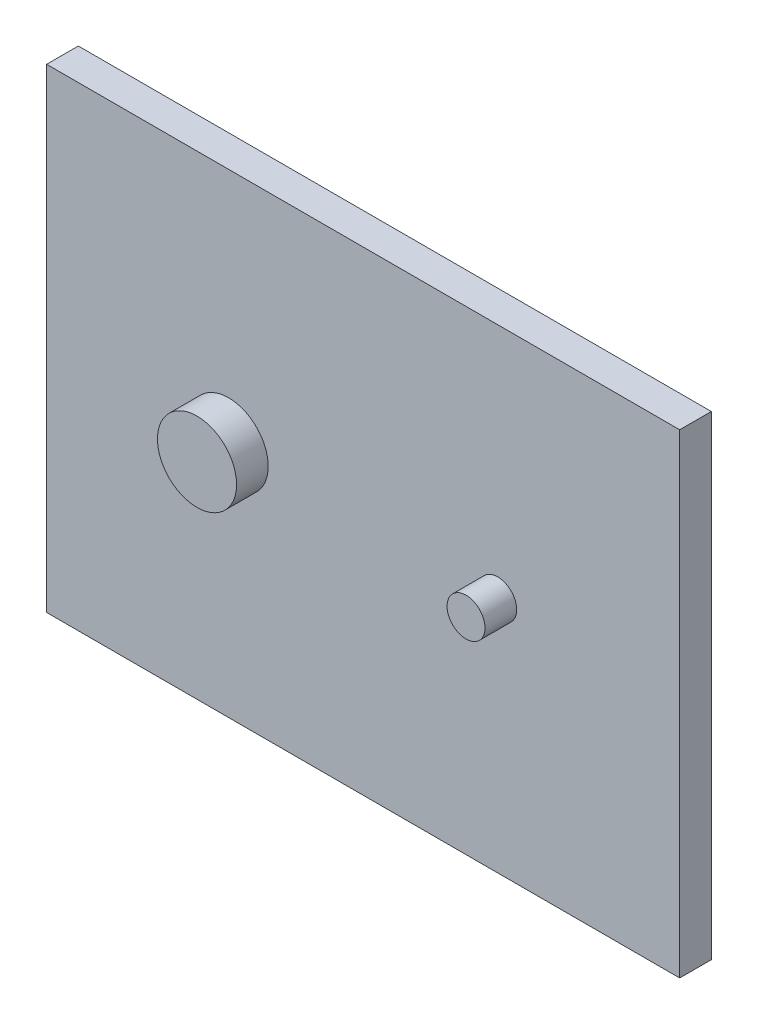
SolidWorks part; units mm, degrees
ref_plane "Front" through (0, 0, 0) normal (0, 0, 1) x (1, 0, 0)
ref_plane "Top" through (0, 0, 0) normal (0, 1, 0) x (1, 0, 0)
ref_plane "Right" through (0, 0, 0) normal (1, 0, 0) x (0, 0, -1)
sketch "Sketch1" plane through (0, 0, 0) normal (0, 0, 1) x (1, 0, 0)
  line L1 (-127.9213, 43.728) -> (72.0787, 43.728)
  line L2 (-127.9213, 43.728) -> (-127.9213, -106.272)
  line L3 (-127.9213, -106.272) -> (72.0787, -106.272)
  line L4 (72.0787, 43.728) -> (72.0787, -106.272)
  dimension "D1" = 200
  dimension "D2" = 150
extrude "Extrude1" add sketch "Sketch1" along normal blind 10
sketch "Sketch2" plane through (0, 0, 10) normal (0, 0, 1) x (1, 0, 0)
  line L0 (72.0787, 43.728) -> (-127.9213, 43.728) construction
  line L1 (72.0787, 43.728) -> (-127.9213, 43.728) construction
  circle A0 centre (-70.4213, -31.272) radius 12.5
  circle A1 centre (14.5787, -31.272) radius 6
  point P8 (-27.9213, 43.728)
  dimension "D1" = 25
  dimension "D2" = 12
  dimension "D3" = 85
  dimension "D4" = 42.5
  dimension "D5" = 75
extrude "Extrude2" add sketch "Sketch2" along normal blind 10
